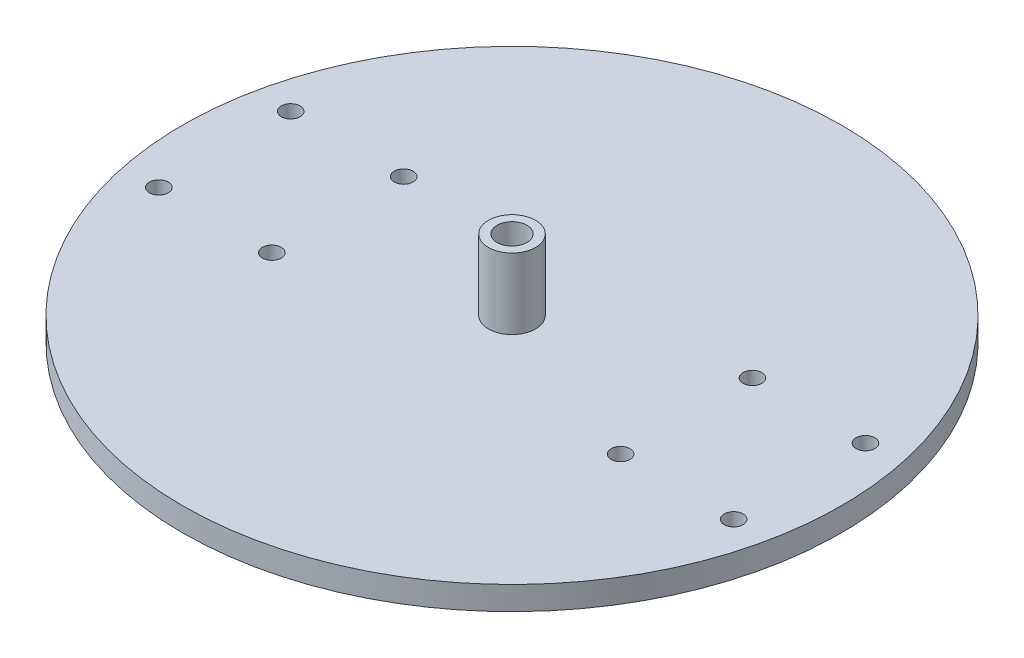
SolidWorks part; units mm, degrees
ref_plane "Front Plane" through (0, 0, 0) normal (0, 0, 1) x (1, 0, 0)
ref_plane "Top Plane" through (0, 0, 0) normal (0, 1, 0) x (1, 0, 0)
ref_plane "Right Plane" through (0, 0, 0) normal (1, 0, 0) x (0, 0, -1)
sketch "Sketch1" plane through (0, 0, 0) normal (0, 1, 0) x (1, 0, 0)
  circle A0 centre (0, 0) radius 3.175
  circle A1 centre (0, 0) radius 70
extrude "Boss-Extrude2" add sketch "Sketch1" along normal blind 5
sketch "Sketch2" plane through (0, 5, 0) normal (0, 1, 0) x (1, 0, 0)
  circle A0 centre (0, 0) radius 5
  circle A1 centre (0, 0) radius 3.175
extrude "Boss-Extrude4" add sketch "Sketch2" along normal blind 15
sketch "Sketch5" plane through (0, 5, 0) normal (0, 1, 0) x (1, 0, 0)
  line L0 (0, 0) -> (0, 70)
  circle A0 centre (-61.0418, 14.0332) radius 2
  circle A1 centre (-37.0418, 14.0332) radius 2
  circle A2 centre (-61.0418, -13.9668) radius 2
  circle A3 centre (-37.0418, -13.9668) radius 2
  circle A4 centre (0, 0) radius 70 construction
  circle A5 centre (37.0418, -13.9668) radius 2
  circle A6 centre (61.0418, -13.9668) radius 2
  circle A7 centre (37.0418, 14.0332) radius 2
  circle A8 centre (61.0418, 14.0332) radius 2
extrude "Cut-Extrude4" cut sketch "Sketch5" against normal through all contours A0 | A1 | A2 | A3 | A7 | A8 | A5 | A6
